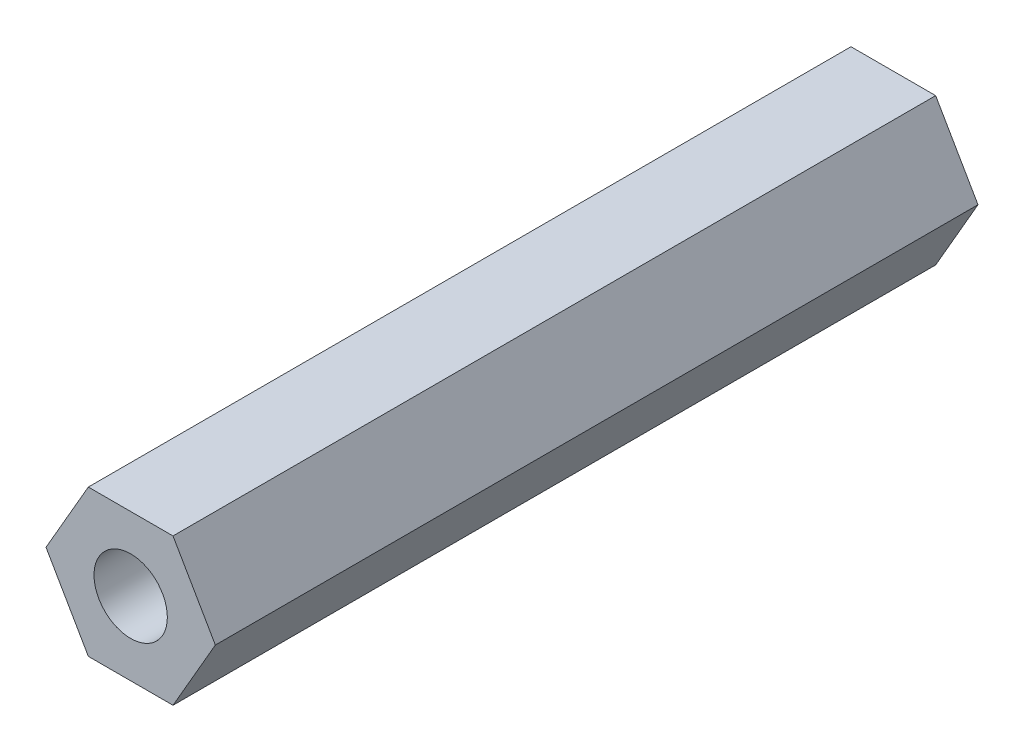
SolidWorks part; units mm, degrees
ref_plane "Front Plane" through (0, 0, 0) normal (0, 0, 1) x (1, 0, 0)
ref_plane "Top Plane" through (0, 0, 0) normal (0, 1, 0) x (1, 0, 0)
ref_plane "Right Plane" through (0, 0, 0) normal (1, 0, 0) x (0, 0, -1)
sketch "Sketch1" plane through (0, 0, 0) normal (0, 0, 1) x (1, 0, 0)
  line L1 (7.3323, 0) -> (3.6662, 6.35)
  line L2 (3.6662, 6.35) -> (-3.6662, 6.35)
  line L3 (-3.6662, 6.35) -> (-7.3323, 0)
  line L4 (-7.3323, 0) -> (-3.6662, -6.35)
  line L5 (-3.6662, -6.35) -> (3.6662, -6.35)
  line L6 (3.6662, -6.35) -> (7.3323, 0)
  circle A0 centre (0, 0) radius 6.35 construction
  circle A1 centre (0, 0) radius 3.175
  dimension "D1" = 12.7
  dimension "D2" = 6.35
extrude "Boss-Extrude1" add sketch "Sketch1" along normal blind 66.04
